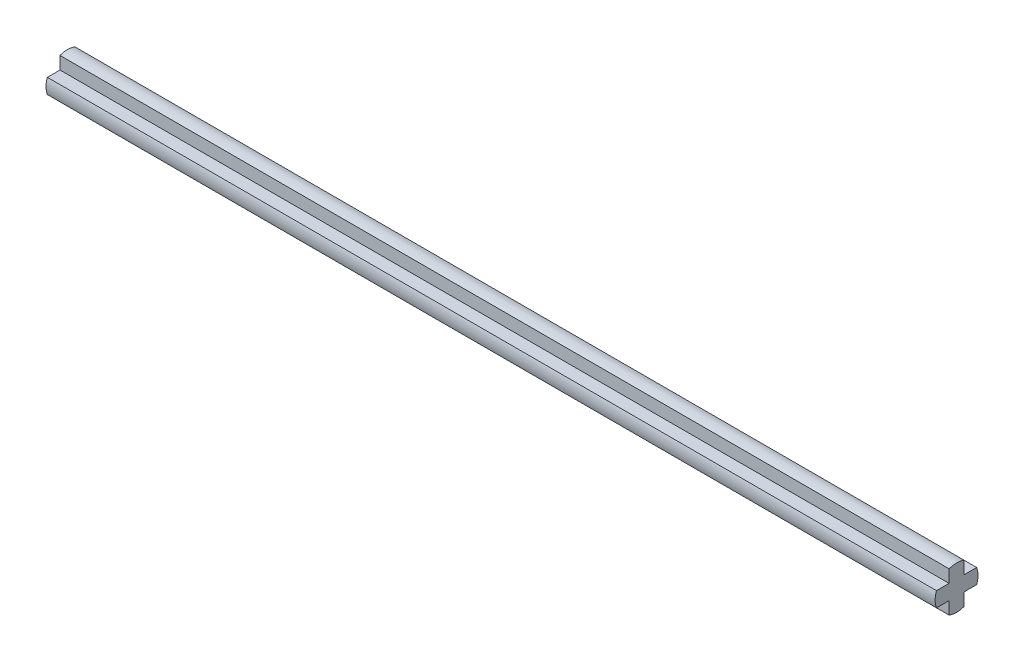
SolidWorks part; units mm, degrees
ref_plane "Front Plane" through (0, 0, 0) normal (0, 0, 1) x (1, 0, 0)
ref_plane "Top Plane" through (0, 0, 0) normal (0, 1, 0) x (1, 0, 0)
ref_plane "Right Plane" through (0, 0, 0) normal (1, 0, 0) x (0, 0, -1)
sketch "Sketch1" plane through (0, 0, 0) normal (1, 0, 0) x (0, 0, -1)
  line L0 (-2.1564, 0.8) -> (-0.8, 0.8)
  line L1 (2.1564, -0.8) -> (-2.1564, -0.8) construction
  line L2 (2.1564, -0.8) -> (2.1564, 0.8) construction
  line L3 (2.1564, 0.8) -> (-2.1564, 0.8) construction
  line L4 (-2.1564, -0.8) -> (-2.1564, 0.8) construction
  line L5 (2.1564, -0.8) -> (-2.1564, 0.8) construction
  line L6 (2.1564, 0.8) -> (-2.1564, -0.8) construction
  line L7 (-0.8, -2.1564) -> (0.8, -2.1564) construction
  line L8 (-0.8, -2.1564) -> (-0.8, 2.1564) construction
  line L9 (-0.8, 2.1564) -> (0.8, 2.1564) construction
  line L10 (0.8, -2.1564) -> (0.8, 2.1564) construction
  line L11 (-0.8, -2.1564) -> (0.8, 2.1564) construction
  line L12 (-0.8, 2.1564) -> (0.8, -2.1564) construction
  line L13 (-0.8, 0.8) -> (-0.8, 2.1564)
  line L14 (0.8, 2.1564) -> (0.8, 0.8)
  line L15 (0.8, 0.8) -> (2.1564, 0.8)
  line L16 (2.1564, -0.8) -> (0.8, -0.8)
  line L17 (0.8, -0.8) -> (0.8, -2.1564)
  line L18 (-0.8, -2.1564) -> (-0.8, -0.8)
  line L19 (-0.8, -0.8) -> (-2.1564, -0.8)
  circle A0 centre (0, 0) radius 2.3 construction
  spline S0 degree 2 poles (-2.1564, -0.8) (-2.4436, 0) (-2.1564, 0.8) knots 0 0 0 1 1 1
  spline S1 degree 2 poles (-0.8, 2.1564) (0, 2.4436) (0.8, 2.1564) knots 0 0 0 1 1 1
  spline S2 degree 2 poles (2.1564, 0.8) (2.4436, 0) (2.1564, -0.8) knots 0 0 0 1 1 1
  spline S3 degree 2 poles (0.8, -2.1564) (0, -2.4436) (-0.8, -2.1564) knots 0 0 0 1 1 1
  point P18 (0, 0)
  dimension "D1" = 4.6
  dimension "D2" = 1.6
  dimension "D3" = 1.6
extrude "Boss-Extrude1" add sketch "Sketch1" along normal blind 95.4
